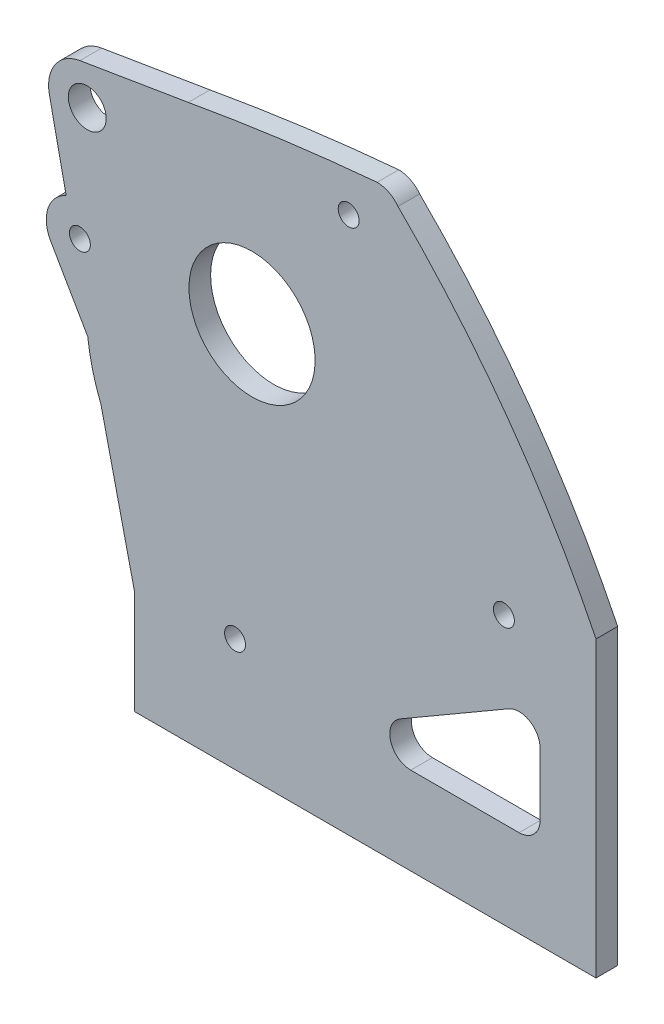
SolidWorks part; units mm, degrees
ref_plane "Front Plane" through (0, 0, 0) normal (0, 0, 1) x (1, 0, 0)
ref_plane "Top Plane" through (0, 0, 0) normal (0, 1, 0) x (1, 0, 0)
ref_plane "Right Plane" through (0, 0, 0) normal (1, 0, 0) x (0, 0, -1)
sketch "Sketch1" plane through (0, 0, 0) normal (0, 0, 1) x (1, 0, 0)
  line L0 (-37.9718, 75.9705) -> (-37.9721, 75.9723)
  line L1 (-37.9721, 75.9723) -> (-37.9718, 75.9705)
  line L2 (-37.9718, 75.9705) -> (-68.6826, 70.8743)
  line L3 (-77.4179, 58.0635) -> (-72.6294, 35.5352)
  line L4 (-72.6294, 35.5352) -> (-73.507, 35.0284)
  line L5 (-77.0209, 21.9146) -> (-66.4553, 3.6145)
  line L6 (-62.6518, -11.3699) -> (-53.0658, -52.8915)
  line L7 (-53.0658, -52.8915) -> (-53.0555, -82.5915)
  line L8 (-53.0555, -82.5915) -> (78.9445, -82.5915)
  line L9 (78.9445, -82.5915) -> (78.9445, -50.1915)
  line L10 (78.9445, -50.1915) -> (78.9445, 1.4085)
  line L11 (-37.7022, 76.0152) -> (-37.9718, 75.9705)
  line L12 (62.9445, -33.5916) -> (62.9445, -51.5916)
  line L13 (56.9445, -57.5916) -> (25.9445, -57.5916)
  line L14 (22.9317, -46.4028) -> (53.9317, -28.4028)
  circle A0 centre (-66.5927, 60.2381) radius 5.4293
  circle A1 centre (-19.4555, 30.2084) radius 18.05
  circle A2 centre (8.196, 71.1146) radius 3
  circle A3 centre (-24.307, -50.1885) radius 3
  circle A4 centre (-68.707, 26.7146) radius 3
  circle A5 centre (52.596, -5.7885) radius 3
  circle A6 centre (-19.4555, 30.2084) radius 6.5
  arc A7 (-68.6826, 70.8743) -> (-77.4179, 58.0635) centre (-66.9268, 60.2935) ccw
  arc A8 (-73.507, 35.0284) -> (-77.0209, 21.9146) centre (-68.707, 26.7146) ccw
  arc A9 (-66.4553, 3.6145) -> (-62.6518, -11.3699) centre (-8.0555, 10.4631) ccw
  arc A10 (78.9445, 1.4085) -> (22.3086, 80.229) centre (-182.3276, -126.5687) ccw
  arc A11 (22.3086, 80.229) -> (16.3086, 83.229) centre (16.2726, 75.657) ccw
  arc A12 (16.3086, 83.229) -> (-37.7022, 76.0152) centre (70.1689, -525.8329) ccw
  arc A13 (62.9445, -33.5916) -> (53.9317, -28.4028) centre (56.9445, -33.5916) ccw
  arc A14 (56.9445, -57.5916) -> (62.9445, -51.5916) centre (56.9445, -51.5916) ccw
  arc A15 (22.9317, -46.4028) -> (25.9445, -57.5916) centre (25.9445, -51.5916) ccw
extrude "Boss-Extrude1" add sketch "Sketch1" along normal blind 6.2 contours A11 A12 L11 L2 A7 L3 L4 A8 L5 A9 L6 L7 L8 L9 L10 A10 A15 L14 A13 L12 A14 L13 A0 A1 A2 A3 A4 A5
